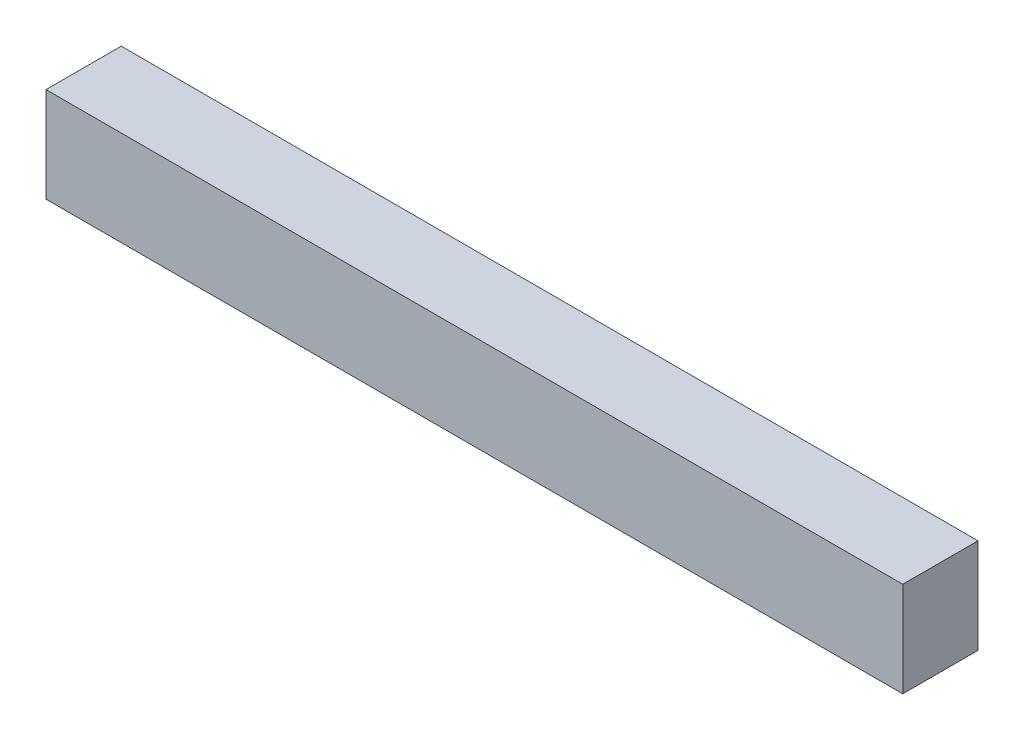
SolidWorks part; units mm, degrees
ref_plane "Front Plane" through (0, 0, 0) normal (0, 0, 1) x (1, 0, 0)
ref_plane "Top Plane" through (0, 0, 0) normal (0, 1, 0) x (1, 0, 0)
ref_plane "Right Plane" through (0, 0, 0) normal (1, 0, 0) x (0, 0, -1)
sketch "Sketch1" plane through (0, 0, 0) normal (0, 0, 1) x (1, 0, 0)
  line L1 (-82.55, 9.145) -> (82.55, 9.145)
  line L2 (-82.55, 9.145) -> (-82.55, -9.145)
  line L3 (-82.55, -9.145) -> (82.55, -9.145)
  line L4 (82.55, 9.145) -> (82.55, -9.145)
  line L5 (-82.55, 9.145) -> (82.55, -9.145) construction
  line L6 (-82.55, -9.145) -> (82.55, 9.145) construction
  point P0 (0, 0)
  dimension "D1" = 165.1
  dimension "D2" = 18.29
extrude "Boss-Extrude2" add sketch "Sketch1" along normal blind 14.5
sketch "Sketch3" plane through (0, 9.145, 0) normal (0, 1, 0) x (1, 0, 0)
  line L0 (-82.55, -7.25) -> (82.55, -7.25) construction
  line L1 (-78.55, -4.71) -> (-73.47, -4.71)
  line L2 (-78.55, -4.71) -> (-78.55, -9.79)
  line L3 (-78.55, -9.79) -> (-73.47, -9.79)
  line L4 (-73.47, -4.71) -> (-73.47, -9.79)
  line L5 (-78.55, -4.71) -> (-73.47, -9.79) construction
  line L6 (-78.55, -9.79) -> (-73.47, -4.71) construction
  line L7 (-82.55, -14.5) -> (-82.55, 0) construction
  line L8 (82.55, -14.5) -> (82.55, 0) construction
  line L10 (-81.09, -0.775) -> (-70.93, -0.775) construction
  line L11 (-81.09, -0.775) -> (-81.09, -13.725) construction
  line L12 (-81.09, -13.725) -> (-70.93, -13.725) construction
  line L13 (-70.93, -0.775) -> (-70.93, -13.725) construction
  line L14 (-81.09, -0.775) -> (-70.93, -13.725) construction
  line L15 (-81.09, -13.725) -> (-70.93, -0.775) construction
  line L47 (82.55, 0) -> (-82.55, 0) construction
  line L48 (-66.2659, -4.71) -> (-61.1859, -4.71)
  line L49 (-66.2659, -4.71) -> (-66.2659, -9.79)
  line L50 (-66.2659, -9.79) -> (-61.1859, -9.79)
  line L51 (-61.1859, -4.71) -> (-61.1859, -9.79)
  line L52 (-66.2659, -4.71) -> (-61.1859, -9.79) construction
  line L53 (-66.2659, -9.79) -> (-61.1859, -4.71) construction
  line L54 (-54.8879, -4.71) -> (-49.8079, -4.71)
  line L55 (-54.8879, -4.71) -> (-54.8879, -9.79)
  line L56 (-54.8879, -9.79) -> (-49.8079, -9.79)
  line L57 (-49.8079, -4.71) -> (-49.8079, -9.79)
  line L58 (-54.8879, -4.71) -> (-49.8079, -9.79) construction
  line L59 (-54.8879, -9.79) -> (-49.8079, -4.71) construction
  line L60 (-2.54, -4.71) -> (2.54, -4.71)
  line L61 (-2.54, -4.71) -> (-2.54, -9.79)
  line L62 (-2.54, -9.79) -> (2.54, -9.79)
  line L63 (2.54, -4.71) -> (2.54, -9.79)
  line L64 (-2.54, -4.71) -> (2.54, -9.79) construction
  line L65 (-2.54, -9.79) -> (2.54, -4.71) construction
  line L66 (-14.6459, -4.71) -> (-9.5659, -4.71)
  line L67 (-14.6459, -4.71) -> (-14.6459, -9.79)
  line L68 (-14.6459, -9.79) -> (-9.5659, -9.79)
  line L69 (-9.5659, -4.71) -> (-9.5659, -9.79)
  line L70 (-14.6459, -4.71) -> (-9.5659, -9.79) construction
  line L71 (-14.6459, -9.79) -> (-9.5659, -4.71) construction
  line L72 (9.4274, -4.71) -> (14.5074, -4.71)
  line L73 (9.4274, -4.71) -> (9.4274, -9.79)
  line L74 (9.4274, -9.79) -> (14.5074, -9.79)
  line L75 (14.5074, -4.71) -> (14.5074, -9.79)
  line L76 (9.4274, -4.71) -> (14.5074, -9.79) construction
  line L77 (9.4274, -9.79) -> (14.5074, -4.71) construction
  line L78 (61.696, -4.71) -> (56.616, -4.71)
  line L79 (61.696, -4.71) -> (61.696, -9.79)
  line L80 (61.696, -9.79) -> (56.616, -9.79)
  line L81 (56.616, -4.71) -> (56.616, -9.79)
  line L82 (61.696, -4.71) -> (56.616, -9.79) construction
  line L83 (61.696, -9.79) -> (56.616, -4.71) construction
  line L84 (68.8323, -4.71) -> (73.9123, -4.71)
  line L85 (68.8323, -4.71) -> (68.8323, -9.79)
  line L86 (68.8323, -9.79) -> (73.9123, -9.79)
  line L87 (73.9123, -4.71) -> (73.9123, -9.79)
  line L88 (68.8323, -4.71) -> (73.9123, -9.79) construction
  line L89 (68.8323, -9.79) -> (73.9123, -4.71) construction
  line L90 (50.7971, -4.71) -> (45.7171, -4.71)
  line L91 (50.7971, -4.71) -> (50.7971, -9.79)
  line L92 (50.7971, -9.79) -> (45.7171, -9.79)
  line L93 (45.7171, -4.71) -> (45.7171, -9.79)
  line L94 (50.7971, -4.71) -> (45.7171, -9.79) construction
  line L95 (50.7971, -9.79) -> (45.7171, -4.71) construction
  line L96 (-82.5294, 12.3694) -> (0.0206, 12.3694)
  line L97 (-82.5294, 12.3694) -> (-82.5294, -0.0864)
  line L98 (-82.5294, -0.0864) -> (0.0206, -0.0864)
  line L99 (0.0206, 12.3694) -> (0.0206, -0.0864)
  line L100 (-82.5294, 12.3694) -> (0.0206, -0.0864) construction
  line L101 (-82.5294, -0.0864) -> (0.0206, 12.3694) construction
  line L102 (0.1104, 12.7287) -> (82.6604, 12.7287)
  line L103 (0.1104, 12.7287) -> (0.1104, 0)
  line L104 (0.1104, 0) -> (82.6604, 0)
  line L105 (82.6604, 12.7287) -> (82.6604, 0)
  line L106 (0.1104, 12.7287) -> (82.6604, 0) construction
  line L107 (0.1104, 0) -> (82.6604, 12.7287) construction
  line L110 (-68.8059, -0.775) -> (-58.6459, -0.775)
  line L111 (-68.8059, -0.775) -> (-68.8059, -13.725)
  line L112 (-68.8059, -13.725) -> (-58.6459, -13.725)
  line L113 (-58.6459, -0.775) -> (-58.6459, -13.725)
  line L114 (-68.8059, -0.775) -> (-58.6459, -13.725) construction
  line L115 (-68.8059, -13.725) -> (-58.6459, -0.775) construction
  line L116 (-57.4279, -0.775) -> (-47.2679, -0.775)
  line L117 (-57.4279, -0.775) -> (-57.4279, -13.725)
  line L118 (-57.4279, -13.725) -> (-47.2679, -13.725)
  line L119 (-47.2679, -0.775) -> (-47.2679, -13.725)
  line L120 (-57.4279, -0.775) -> (-47.2679, -13.725) construction
  line L121 (-57.4279, -13.725) -> (-47.2679, -0.775) construction
  line L122 (-17.1859, -0.775) -> (-7.0259, -0.775)
  line L123 (-17.1859, -0.775) -> (-17.1859, -13.725)
  line L124 (-17.1859, -13.725) -> (-7.0259, -13.725)
  line L125 (-7.0259, -0.775) -> (-7.0259, -13.725)
  line L126 (-17.1859, -0.775) -> (-7.0259, -13.725) construction
  line L127 (-17.1859, -13.725) -> (-7.0259, -0.775) construction
  line L128 (-5.08, -0.775) -> (5.08, -0.775)
  line L129 (-5.08, -0.775) -> (-5.08, -13.725)
  line L130 (-5.08, -13.725) -> (5.08, -13.725)
  line L131 (5.08, -0.775) -> (5.08, -13.725)
  line L132 (-5.08, -0.775) -> (5.08, -13.725) construction
  line L133 (-5.08, -13.725) -> (5.08, -0.775) construction
  line L134 (6.8874, -0.775) -> (17.0474, -0.775)
  line L135 (6.8874, -0.775) -> (6.8874, -13.725)
  line L136 (6.8874, -13.725) -> (17.0474, -13.725)
  line L137 (17.0474, -0.775) -> (17.0474, -13.725)
  line L138 (6.8874, -0.775) -> (17.0474, -13.725) construction
  line L139 (6.8874, -13.725) -> (17.0474, -0.775) construction
  line L140 (43.1771, -0.775) -> (53.3371, -0.775)
  line L141 (43.1771, -0.775) -> (43.1771, -13.725)
  line L142 (43.1771, -13.725) -> (53.3371, -13.725)
  line L143 (53.3371, -0.775) -> (53.3371, -13.725)
  line L144 (43.1771, -0.775) -> (53.3371, -13.725) construction
  line L145 (43.1771, -13.725) -> (53.3371, -0.775) construction
  line L146 (54.076, -0.775) -> (64.236, -0.775)
  line L147 (54.076, -0.775) -> (54.076, -13.725)
  line L148 (54.076, -13.725) -> (64.236, -13.725)
  line L149 (64.236, -0.775) -> (64.236, -13.725)
  line L150 (54.076, -0.775) -> (64.236, -13.725) construction
  line L151 (54.076, -13.725) -> (64.236, -0.775) construction
  line L152 (66.2923, -0.775) -> (76.4523, -0.775)
  line L153 (66.2923, -0.775) -> (66.2923, -13.725)
  line L154 (66.2923, -13.725) -> (76.4523, -13.725)
  line L155 (76.4523, -0.775) -> (76.4523, -13.725)
  line L156 (66.2923, -0.775) -> (76.4523, -13.725) construction
  line L157 (66.2923, -13.725) -> (76.4523, -0.775) construction
  point P0 (-76.01, -7.25)
  point P11 (-52.3479, -7.25)
  point P12 (-76.01, -7.25)
  point P13 (-63.7259, -7.25)
  point P26 (0, -7.25)
  point P31 (-12.1059, -7.25)
  point P36 (11.9674, -7.25)
  point P41 (59.156, -7.25)
  point P46 (71.3723, -7.25)
  point P51 (48.2571, -7.25)
  point P56 (-41.2544, 6.1415)
  point P61 (41.3854, 6.3644)
  point P66 (-52.3479, -7.25)
  point P71 (-63.7259, -7.25)
  point P78 (-12.1059, -7.25)
  point P83 (0, -7.25)
  point P88 (11.9674, -7.25)
  point P93 (48.2571, -7.25)
  point P98 (59.156, -7.25)
  point P103 (71.3723, -7.25)
  dimension "D1" = 5.08
  dimension "D2" = 5.08
  dimension "D3" = 12.95
  dimension "D4" = 10.16
  dimension "D5" = 4
  dimension "D6" = 82.55
  dimension "D7" = 82.55
  dimension "D8" = 5.08
  dimension "D9" = 10.16
  dimension "D10" = 5.08
  dimension "D11" = 10.16
  dimension "D12" = 10.16
  dimension "D13" = 10.16
  dimension "D14" = 10.16
  dimension "D15" = 10.16
  dimension "D16" = 10.16
  dimension "D17" = 10.16
